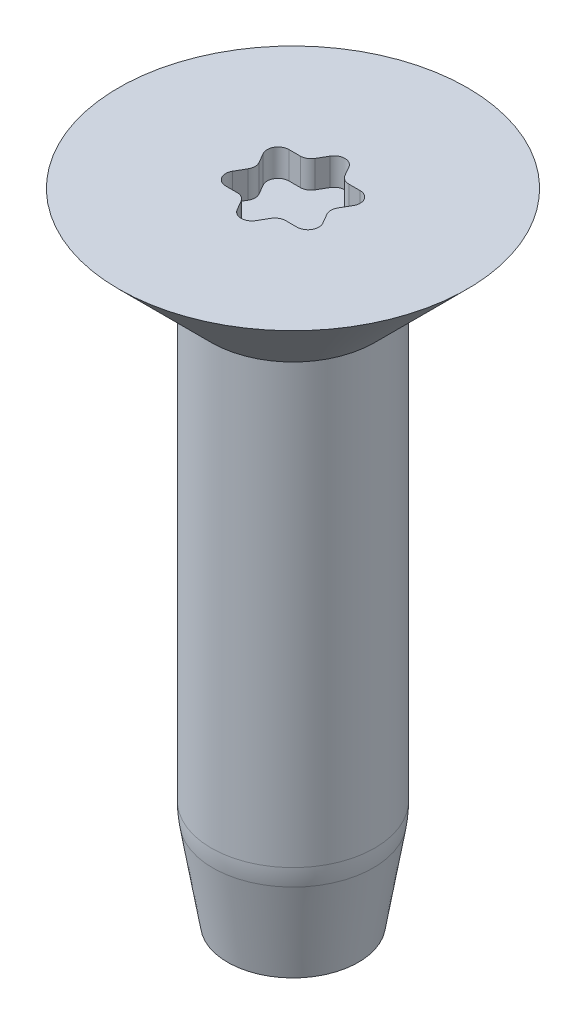
SolidWorks part; units mm, degrees
ref_plane "Front" through (0, 0, 0) normal (0, 0, 1) x (1, 0, 0)
ref_plane "Top" through (0, 0, 0) normal (0, 1, 0) x (1, 0, 0)
ref_plane "Right" through (0, 0, 0) normal (1, 0, 0) x (0, 0, -1)
sketch "Sketch1" plane through (0, 0, 0) normal (0, 0, 1) x (1, 0, 0)
  line L0 (0, 0) -> (0, 1.7)
  line L1 (0, 1.7) -> (3.2, 1.7)
  line L2 (3.2, 1.7) -> (1.5, 0)
  line L3 (1.5, 0) -> (0, 0)
  dimension "D1" = 1.7
  dimension "D2" = 45
  dimension "D3" = 1.5
ref_axis "Axis1" through (0, 50, 0) along (0, -1, 0)
revolve "Revolve1" add sketch "Sketch1" angle 360 about axis through (0, 50, 0) along (0, -1, 0)
sketch "Sketch2" plane through (0, 0, 0) normal (0, -1, 0) x (1, 0, 0)
  circle A0 centre (0, 0) radius 1.5
  dimension "D1" = 3
extrude "Boss-Extrude1" add sketch "Sketch2" along normal blind 10
sketch "Sketch3" plane through (0, 0, 0) normal (0, 0, 1) x (1, 0, 0)
  line L0 (0, 0) -> (0, -11.7224) construction
  line L1 (1.5, -8.2) -> (1.2, -10)
  line L2 (1.2, -10) -> (1.5, -10)
  line L3 (1.5, -10) -> (1.5, -8.2)
  line L4 (1.5, -10) -> (1.5, 0) construction
  line L5 (-1.5, -10) -> (1.5, -10) construction
  dimension "D1" = 0.3
  dimension "D2" = 1.8
revolve "Cut-Revolve1" cut sketch "Sketch3" angle 360 about L0
sketch "Sketch4" plane through (0, 1.7, 0) normal (0, 1, 0) x (1, 0, 0)
  line L0 (0, 0) -> (0, 1.9842) construction
  line L1 (0, 0) -> (2.0052, 0) construction
  line L2 (0, 1.1521) -> (0.3303, 0.58)
  line L3 (0, 1.1521) -> (-0.3303, 0.58)
  line L4 (-1, 0.58) -> (-0.3303, 0.58)
  line L5 (1, 0.58) -> (0.6651, 0)
  line L6 (-1, 0.58) -> (-0.6651, 0)
  line L7 (-1, -0.58) -> (-0.3303, -0.58)
  line L8 (-0.6651, 0) -> (-1, -0.58)
  line L9 (-0.3303, -0.58) -> (0, -1.1521)
  line L10 (0.3303, 0.58) -> (1, 0.58)
  line L11 (0.3303, -0.58) -> (0, -1.1521)
  line L12 (0.6651, 0) -> (1, -0.58)
  line L13 (0.3303, -0.58) -> (1, -0.58)
  dimension "D1" = 2
  dimension "D2" = 0.58
extrude "Cut-Extrude1" cut sketch "Sketch4" against normal blind 0.5
fillet "Fillet1" radius 0.2 12 edges at (1, 1.45, -0.58) (0.6651, 1.45, 0) (1, 1.45, 0.58) (0.3303, 1.45, 0.58) (0, 1.45, 1.1521) (-0.3303, 1.45, 0.58) (-1, 1.45, 0.58) (-0.6651, 1.45, 0) (-1, 1.45, -0.58) (0.3303, 1.45, -0.58) (0, 1.45, -1.1521) (-0.3303, 1.45, -0.58)
fillet "Fillet3" radius 2 1 edges at (-1.5, -8.2, 0)
